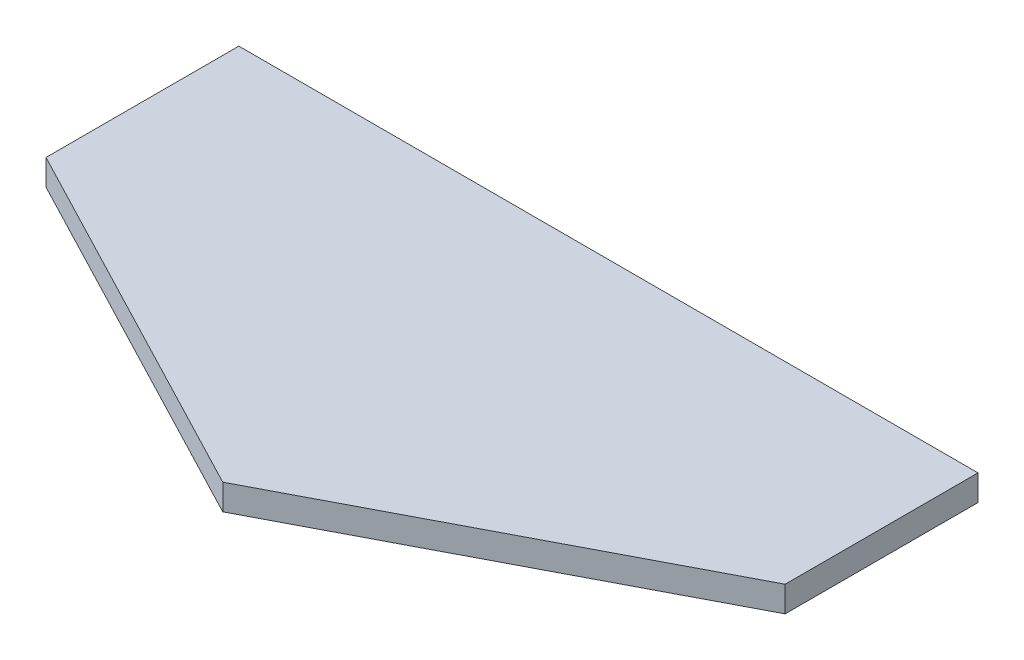
SolidWorks part; units mm, degrees
ref_plane "Front Plane" through (0, 0, 0) normal (0, 0, 1) x (1, 0, 0)
ref_plane "Top Plane" through (0, 0, 0) normal (0, 1, 0) x (1, 0, 0)
ref_plane "Right Plane" through (0, 0, 0) normal (1, 0, 0) x (0, 0, -1)
sketch "Sketch1" plane through (0, 0, 0) normal (0, 1, 0) x (1, 0, 0)
  line L0 (0, -30) -> (57.5, -60)
  line L1 (0, 0) -> (115, 0)
  line L2 (0, 0) -> (0, -30)
  line L3 (0, -30) -> (115, -30)
  line L4 (115, 0) -> (115, -30)
  line L5 (57.5, -60) -> (115, -30)
  line L6 (57.5, -60) -> (57.5, -30) construction
  dimension "D1" = 115
  dimension "D2" = 30
  dimension "D3" = 30
extrude "Boss-Extrude1" add sketch "Sketch1" along normal blind 4 contours L0 L6 L3 | L4 L1 L2 L3 | L6 L5 L3
ref_plane "Plane1" through (57.5, 0, 0) normal (1, 0, 0) x (0, 0, -1)
